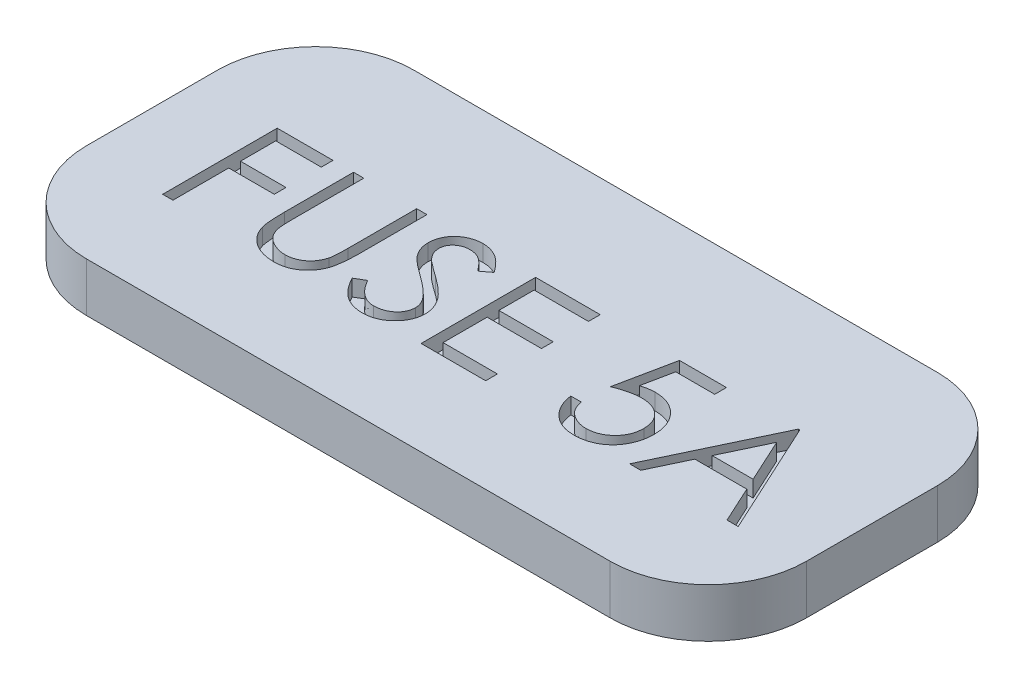
SolidWorks part; units mm, degrees
material "ABS"
ref_plane "Front Plane" through (0, 0, 0) normal (0, 0, 1) x (1, 0, 0)
ref_plane "Top Plane" through (0, 0, 0) normal (0, 1, 0) x (1, 0, 0)
ref_plane "Right Plane" through (0, 0, 0) normal (1, 0, 0) x (0, 0, -1)
sketch "Sketch1" plane through (0, 0, 0) normal (0, 1, 0) x (1, 0, 0)
  line L1 (0, 0) -> (-22, 0)
  line L2 (0, 0) -> (0, -10)
  line L3 (0, -10) -> (-22, -10)
  line L4 (-22, 0) -> (-22, -10)
  dimension "D1" = 10
  dimension "D2" = 22
extrude "Boss-Extrude1" add sketch "Sketch1" along normal blind 1.5
sketch "Sketch2" plane through (0, 1.5, 0) normal (0, 1, 0) x (1, 0, 0)
  line L0 (-22, -10) -> (0, -10) construction
  line L3 (0, -10) -> (0, 0) construction
  text T0 "FUSE 5A"
  dimension "D1" = 2.875
  dimension "D2" = 20
fillet "Fillet1" radius 3 4 edges at (0, 0.75, 0) (0, 0.75, 10) (-22, 0.75, 10) (-22, 0.75, 0)
extrude "Cut-Extrude1" cut sketch "Sketch2" against normal blind 0.5
